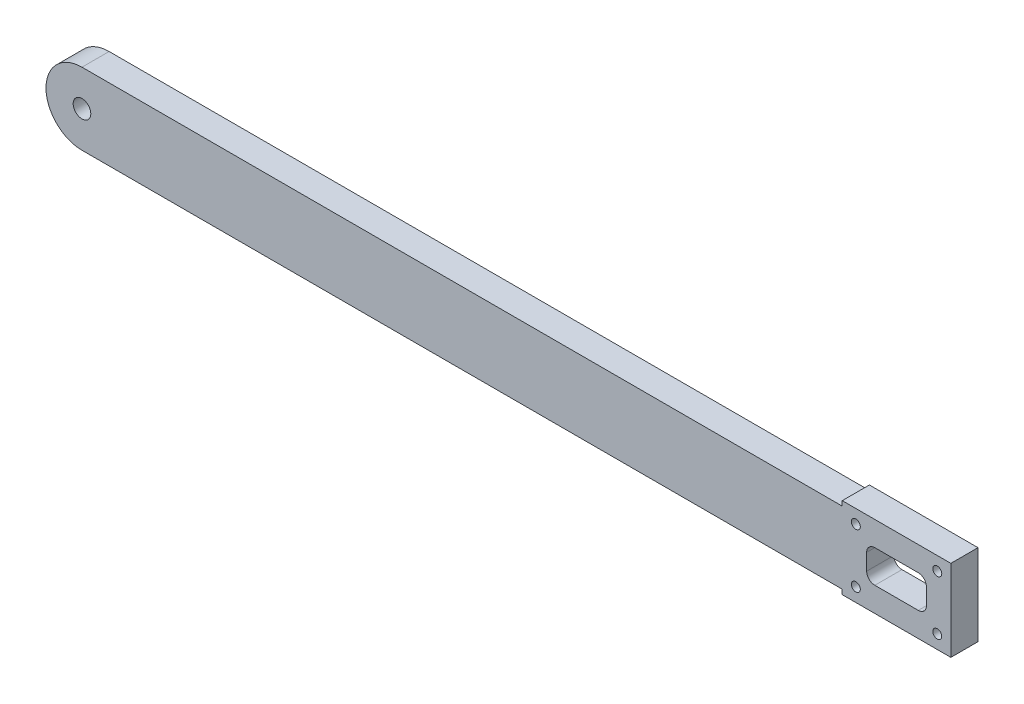
SolidWorks part; units mm, degrees
ref_plane "Front Plane" through (0, 0, 0) normal (0, 0, 1) x (1, 0, 0)
ref_plane "Top Plane" through (0, 0, 0) normal (0, 1, 0) x (1, 0, 0)
ref_plane "Right Plane" through (0, 0, 0) normal (1, 0, 0) x (0, 0, -1)
sketch "Sketch1" plane through (0, 0, 0) normal (0, 0, 1) x (1, 0, 0)
  line L0 (0, 0) -> (300, 0) construction
  line L1 (0, 13.25) -> (300, 13.25)
  line L2 (0, -13.25) -> (300, -13.25)
  line L3 (285, 10) -> (315, 10) construction
  line L4 (280, -15) -> (320, -15)
  line L5 (280, -15) -> (280, 15)
  line L6 (280, 15) -> (320, 15)
  line L7 (320, -15) -> (320, 15)
  line L8 (300, 15) -> (300, -15) construction
  line L9 (280, 0) -> (320, 0) construction
  line L10 (285, 10) -> (285, -10) construction
  line L12 (292, -6) -> (308, -6)
  line L13 (289, -3) -> (289, 3)
  line L14 (292, 6) -> (308, 6)
  line L15 (311, -3) -> (311, 3)
  line L16 (289, -6) -> (311, 6) construction
  line L17 (289, 6) -> (311, -6) construction
  arc A0 (0, 13.25) -> (0, -13.25) centre (0, 0) ccw
  arc A1 (300, -13.25) -> (300, 13.25) centre (300, 0) ccw
  circle A2 centre (0, 0) radius 3.25
  circle A3 centre (285, 10) radius 1.65
  circle A4 centre (315, 10) radius 1.65
  circle A5 centre (285, -10) radius 1.65
  circle A6 centre (315, -10) radius 1.65
  arc A7 (289, 3) -> (292, 6) centre (292, 3) cw
  arc A8 (311, 3) -> (308, 6) centre (308, 3) ccw
  arc A9 (308, -6) -> (311, -3) centre (308, -3) ccw
  arc A10 (292, -6) -> (289, -3) centre (292, -3) cw
  point P3 (150, 0)
  point P10 (300, 0)
  point P21 (300, 10)
  point P25 (285, 0)
  point P26 (300, 0)
  point P30 (300, 0)
  dimension "D1" = 6.5
  dimension "D2" = 10
  dimension "D4" = 3.3
  dimension "D11" = 3
  dimension "D3" = 300
  dimension "D5" = 30
  dimension "D6" = 20
  dimension "D7" = 5
  dimension "D8" = 5
  dimension "D9" = 4
  dimension "D10" = 4
extrude "Main Arm" add sketch "Sketch1" along normal blind 10 contours L1 A0 L2 L5 A2 | L2 A1 L1 L5 A3 A5 | A1 L2 L5 L4 L7 L6 L1 A6 A4
